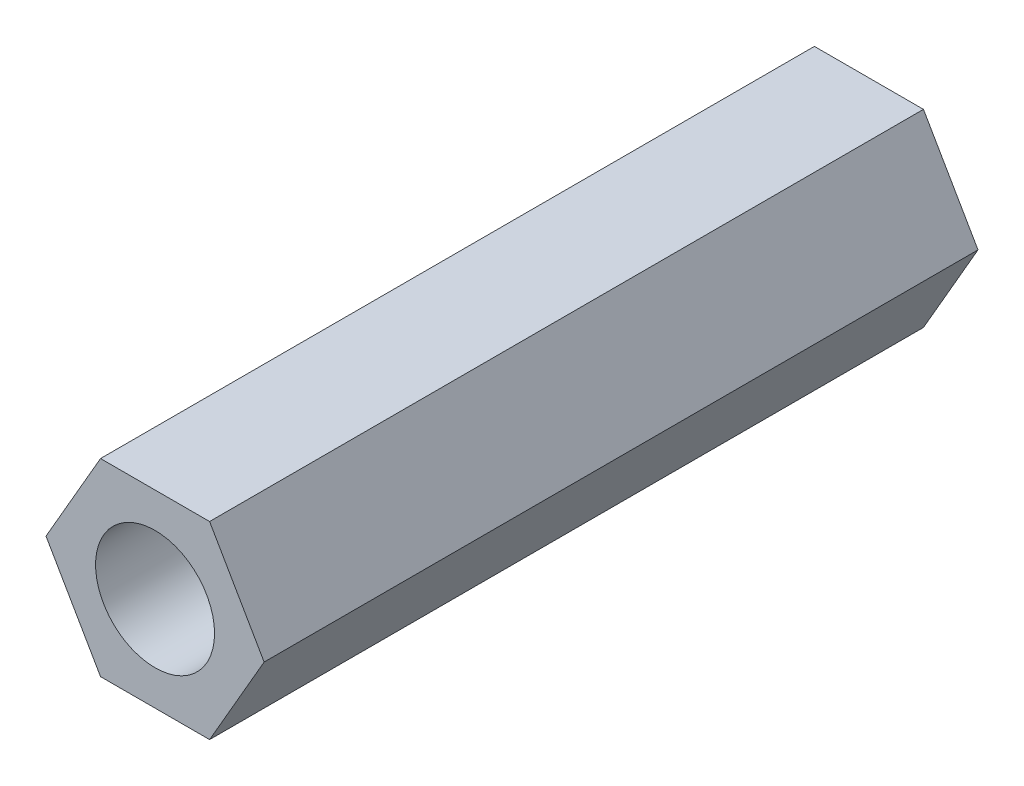
SolidWorks part; units mm, degrees
ref_plane "前视基准面" through (0, 0, 0) normal (0, 0, 1) x (1, 0, 0)
ref_plane "上视基准面" through (0, 0, 0) normal (0, 1, 0) x (1, 0, 0)
ref_plane "右视基准面" through (0, 0, 0) normal (1, 0, 0) x (0, 0, -1)
sketch "Sketch1" plane through (0, 0, 0) normal (0, 0, 1) x (1, 0, 0)
  line L1 (-1.375, 2.3816) -> (-2.75, 0)
  line L2 (-2.75, 0) -> (-1.375, -2.3816)
  line L3 (-1.375, -2.3816) -> (1.375, -2.3816)
  line L4 (1.375, -2.3816) -> (2.75, 0)
  line L5 (2.75, 0) -> (1.375, 2.3816)
  line L6 (1.375, 2.3816) -> (-1.375, 2.3816)
  circle A0 centre (0, 0) radius 2.3816 construction
  circle A1 centre (0, 0) radius 1.5
  dimension "D2" = 3
  dimension "D1" = 5.5
extrude "Boss-Extrude1" add sketch "Sketch1" along normal blind 18
